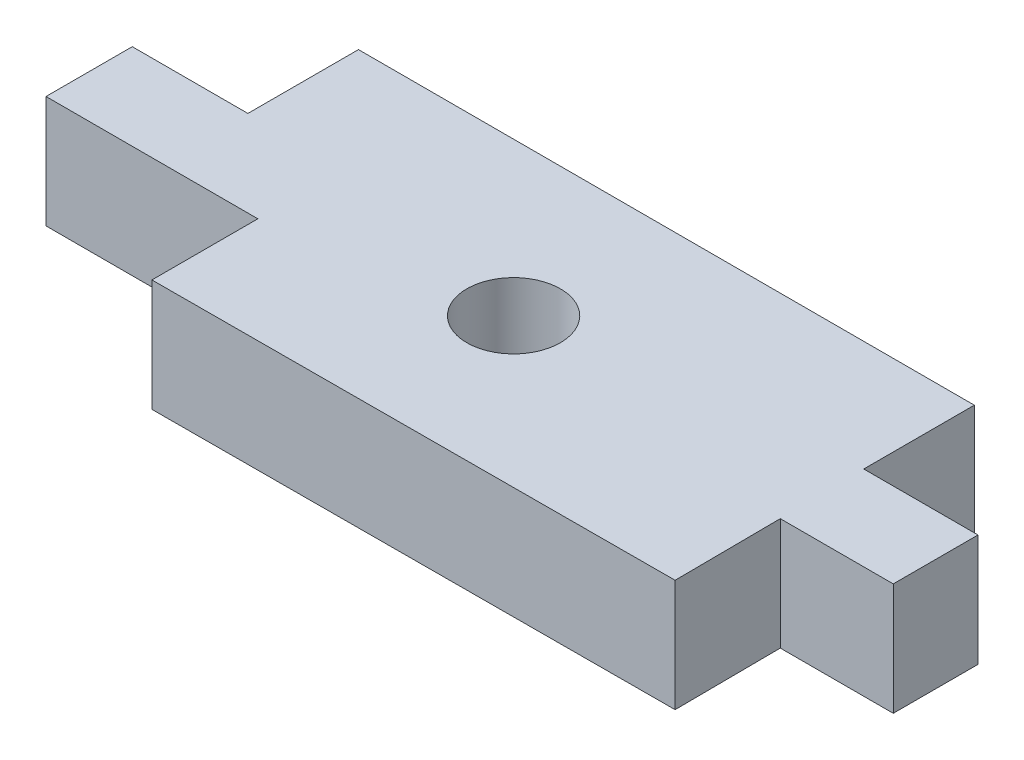
SolidWorks part; units mm, degrees
ref_plane "Front Plane" through (0, 0, 0) normal (0, 0, 1) x (1, 0, 0)
ref_plane "Top Plane" through (0, 0, 0) normal (0, 1, 0) x (1, 0, 0)
ref_plane "Right Plane" through (0, 0, 0) normal (1, 0, 0) x (0, 0, -1)
sketch "Sketch1" plane through (0, 0, 0) normal (0, 1, 0) x (1, 0, 0)
  line L0 (112.7228, 123.5932) -> (127.4976, 123.6364)
  line L2 (112.7229, 126.5933) -> (112.7228, 123.5932)
  line L3 (112.7229, 126.5933) -> (106.7229, 126.5933)
  line L6 (106.7229, 129.0364) -> (106.7229, 126.5933)
  line L7 (106.7229, 129.0364) -> (109.9976, 129.0364)
  line L8 (109.9976, 129.0364) -> (109.9976, 132.1682)
  line L9 (109.9976, 132.1682) -> (127.44, 132.1682)
  line L10 (127.44, 129.0364) -> (127.44, 132.1682)
  line L11 (130.6758, 129.0364) -> (127.44, 129.0364)
  line L12 (130.6758, 129.0364) -> (130.6758, 126.6364)
  line L13 (130.6758, 126.6364) -> (127.476, 126.6364)
  line L14 (127.476, 126.6364) -> (127.4976, 123.6364)
  line L15 (117.7795, 128.7665) -> (119.667, 126.9064) construction
  line L16 (119.6532, 128.825) -> (117.7931, 126.9375) construction
  line L17 (118.7232, 127.8364) -> (131.8632, 127.8364) construction
  circle A5 centre (118.7232, 127.8364) radius 1.325
  dimension "D4" = 1.2
  dimension "D8" = 1.2
  dimension "D9" = 1.2
extrude "Boss-Extrude1" add sketch "Sketch1" along normal blind 3.175
